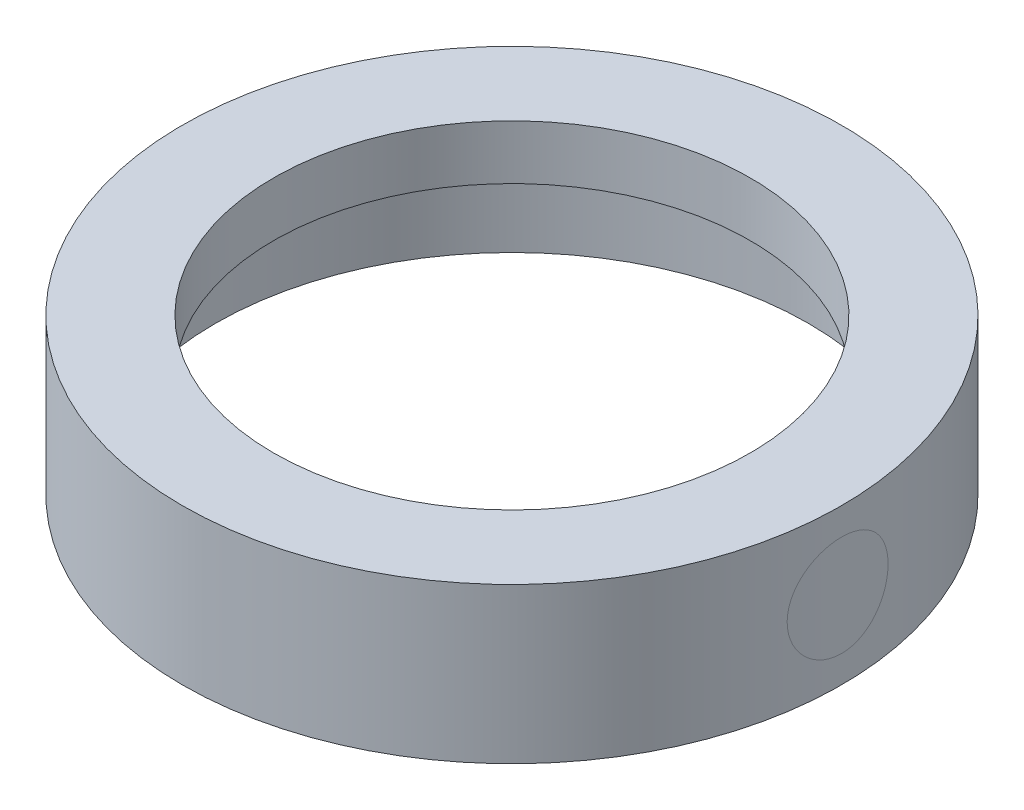
SolidWorks part; units mm, degrees
material "Rubber"
ref_plane "Front Plane" through (0, 0, 0) normal (0, 0, 1) x (1, 0, 0)
ref_plane "Top Plane" through (0, 0, 0) normal (0, 1, 0) x (1, 0, 0)
ref_plane "Right Plane" through (0, 0, 0) normal (1, 0, 0) x (0, 0, -1)
sketch "Sketch1" plane through (0, 0, 0) normal (0, 1, 0) x (1, 0, 0)
  line L0 (0, 0) -> (0, 7.239) construction
  circle A0 centre (0, 0) radius 15.367 construction
  circle A1 centre (0, 0) radius 13.8303 construction
  circle A2 centre (0, 0) radius 11.1125 construction
  point P5 (0, 11.1125)
  point P7 (0, 13.8303)
  point P8 (0, 15.367)
  dimension "ID" = 22.225
  dimension "OD" = 30.734
  dimension "D1" = 27.6606
  dimension "Gasket Height" = 7.239
sketch "Sketch2" plane through (0, 0, 0) normal (1, 0, 0) x (0, 0, -1)
  line L0 (0, 0) -> (7.239, 0) construction
  line L3 (11.1125, 1.0858) -> (11.1125, 3.6195)
  line L4 (11.1125, 3.6195) -> (15.367, 3.6195)
  line L5 (15.367, 3.6195) -> (15.367, -3.6195)
  line L6 (15.367, -3.6195) -> (13.8303, -3.6195)
  line L7 (13.8303, -3.6195) -> (13.8303, 1.0858)
  line L8 (13.8303, 1.0858) -> (11.1125, 1.0858)
  dimension "D1" = 4.7053
ref_axis "Axis1" through (0, 3.9814, 0) along (0, -1, 0)
revolve "Revolve1" add sketch "Sketch2" angle 360 about axis through (0, 3.9814, 0) along (0, -1, 0)
sketch "Sketch3" plane through (0, 0, 0) normal (1, 0, 0) x (0, 0, -1)
  circle A0 centre (0, 0) radius 2.3527
  dimension "D1" = 4.7053
split line "Split Line5"
ref_plane "Plane1" through (0, 1.0858, 0) normal (0, -1, 0) x (-1, 0, 0)
equation "\"D1@Sketch2\"=\"Gasket Height@Sketch1\"*0.65"
equation "\"D1@Sketch1\"=\"OD@Sketch1\"*0.9"
equation "\"D1@Sketch3\"=\"Gasket Height@Sketch1\"*.65"
